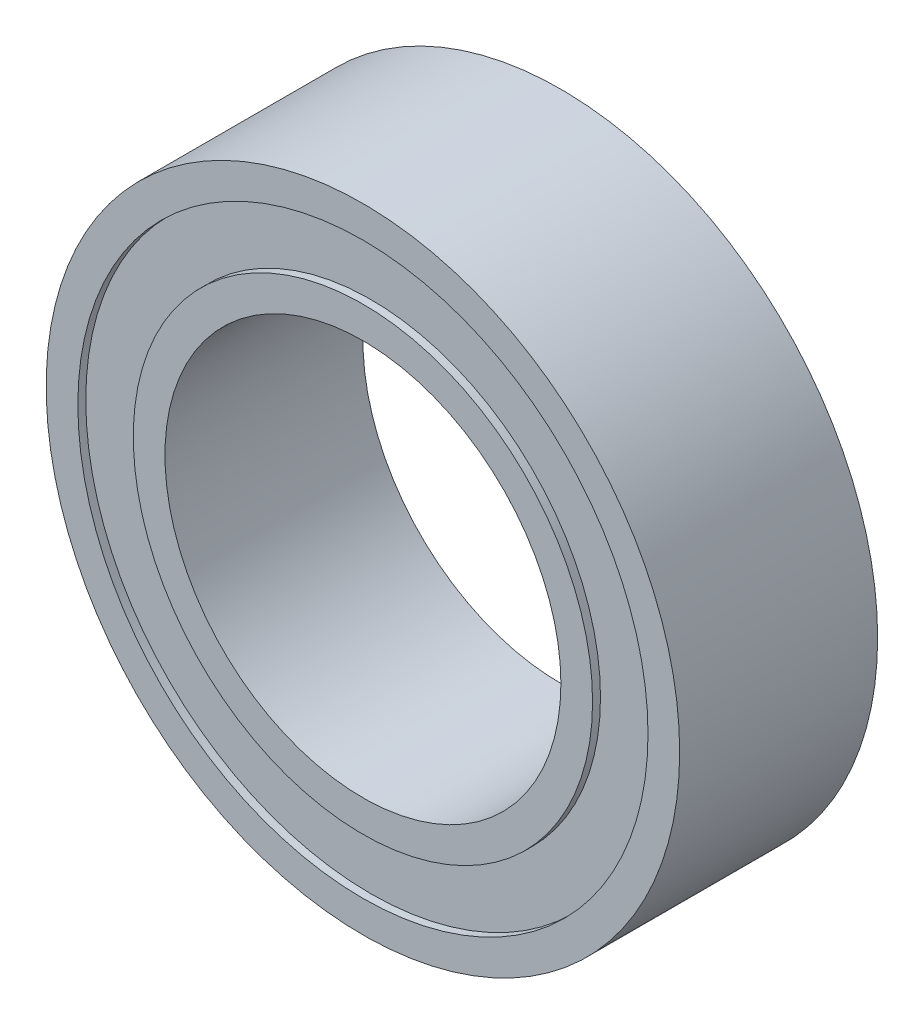
SolidWorks part; units mm, degrees
ref_plane "Front Plane" through (0, 0, 0) normal (0, 0, 1) x (1, 0, 0)
ref_plane "Top Plane" through (0, 0, 0) normal (0, 1, 0) x (1, 0, 0)
ref_plane "Right Plane" through (0, 0, 0) normal (1, 0, 0) x (0, 0, -1)
ref_plane "Plane1"
sketch "Sketch1" plane through (0, 0, 0) normal (0, 0, 1) x (1, 0, 0)
  circle A0 centre (0, 0) radius 4
  circle A1 centre (0, 0) radius 3.6
  circle A2 centre (0, 0) radius 2.9
  circle A3 centre (0, 0) radius 2.5
  dimension "D1" = 8
  dimension "D2" = 5
extrude "Extrusion1" add sketch "Sketch1" along normal blind 2.5 contours A2 A3 | A0 A1
ref_plane "Plane2"
sketch "Sketch2" plane through (0, 0, 0.2) normal (0, 0, 1) x (1, 0, 0)
  circle A0 centre (0, 0) radius 3.6
  circle A1 centre (0, 0) radius 2.9
extrude "Extrusion2" add sketch "Sketch2" along normal blind 2.2 contours A0 A1
